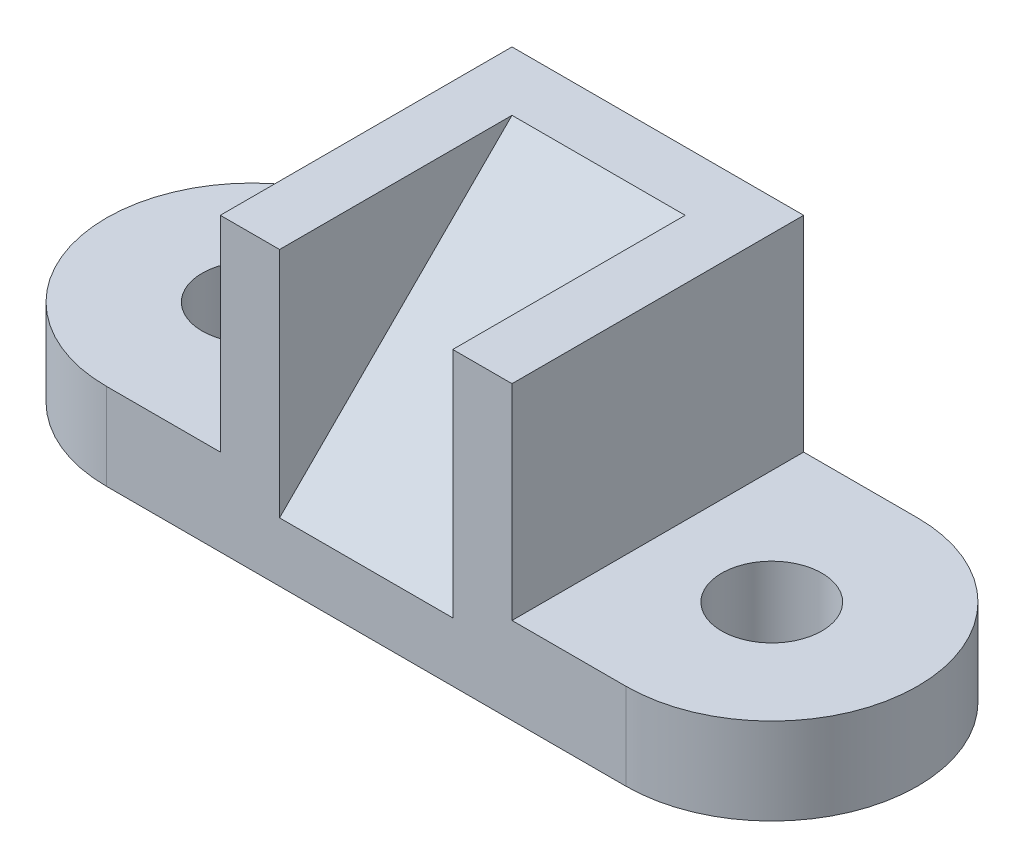
SolidWorks part; units mm, degrees
ref_plane "Front Plane" through (0, 0, 0) normal (0, 0, 1) x (1, 0, 0)
ref_plane "Top Plane" through (0, 0, 0) normal (0, 1, 0) x (1, 0, 0)
ref_plane "Right Plane" through (0, 0, 0) normal (1, 0, 0) x (0, 0, -1)
sketch "Sketch1" plane through (0, 0, 0) normal (0, 1, 0) x (1, 0, 0)
  line L0 (-32, 32) -> (-57, 32)
  line L1 (-32, -32) -> (32, -32)
  line L2 (-32, -32) -> (-32, 32)
  line L3 (-32, 32) -> (32, 32)
  line L4 (32, -32) -> (32, 32)
  line L5 (-32, -32) -> (32, 32) construction
  line L6 (-32, 32) -> (32, -32) construction
  line L7 (-57, -32) -> (-32, -32)
  line L8 (0, 43.3301) -> (0, -57.6363) construction
  line L9 (57, -32) -> (32, -32)
  line L10 (32, 32) -> (57, 32)
  arc A0 (-57, 32) -> (-57, -32) centre (-57, 0) ccw
  circle A1 centre (-57, 0) radius 11
  circle A2 centre (57, 0) radius 11
  arc A3 (57, 32) -> (57, -32) centre (57, 0) cw
  point P0 (0, 0)
  dimension "D3" = 22
  dimension "D1" = 64
  dimension "D2" = 64
  dimension "D4" = 114
extrude "Boss-Extrude1" add sketch "Sketch1" along normal blind 19 contours L0 A0 L7 L2 A1 | L1 L4 L3 L2 | A3 L10 L4 L9 A2
sketch "Sketch2" plane through (0, 19, 0) normal (0, 1, 0) x (1, 0, 0)
  line L0 (57, 32) -> (-57, 32) construction
  line L1 (-32, 32) -> (32, 32)
  line L2 (-32, 32) -> (-32, -32)
  line L3 (-32, -32) -> (32, -32)
  line L4 (32, 32) -> (32, -32)
  line L5 (-57, -32) -> (57, -32) construction
  circle A0 centre (-57, 0) radius 11 construction
  dimension "D1" = 64
  dimension "D2" = 25
extrude "Boss-Extrude2" add sketch "Sketch2" along normal blind 45
sketch "Sketch3" plane through (0, 64, 0) normal (0, 1, 0) x (1, 0, 0)
  line L0 (-32, -32) -> (32, -32) construction
  line L1 (-19, -32) -> (19, -32)
  line L2 (-19, -32) -> (-19, 19)
  line L3 (-19, 19) -> (19, 19)
  line L4 (19, -32) -> (19, 19)
  line L5 (32, 32) -> (-32, 32) construction
  line L6 (32, -32) -> (32, 32) construction
  line L7 (-32, 32) -> (-32, -32) construction
  dimension "D1" = 13
  dimension "D2" = 13
  dimension "D3" = 13
extrude "Cut-Extrude1" cut sketch "Sketch3" against normal blind 51
sketch "Sketch4" plane through (19, 0, 0) normal (-1, 0, 0) x (0, 0, 1)
  line L0 (-19, 64) -> (32, 13)
  line L1 (32, 13) -> (-19, 13)
  line L2 (-19, 13) -> (-19, 64)
extrude "Boss-Extrude3" add sketch "Sketch4" along normal blind 38
